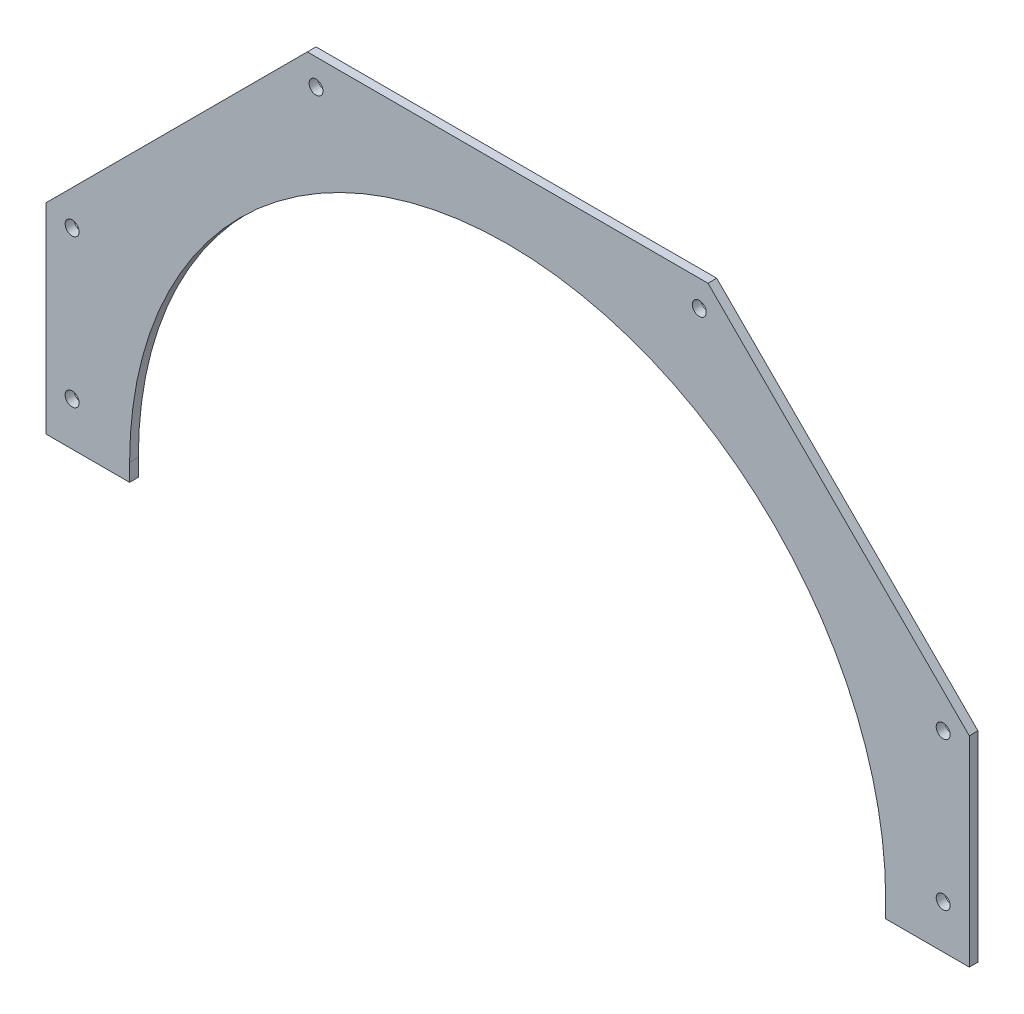
SolidWorks part; units mm, degrees
material "Q235"
ref_plane "前视基准面" through (0, 0, 0) normal (0, 0, 1) x (1, 0, 0)
ref_plane "上视基准面" through (0, 0, 0) normal (0, 1, 0) x (1, 0, 0)
ref_plane "右视基准面" through (0, 0, 0) normal (1, 0, 0) x (0, 0, -1)
sketch "草图1" plane through (0, 0, 0) normal (0, 0, 1) x (1, 0, 0)
  line L1 (0, 0) -> (1060, 0)
  line L2 (0, 0) -> (0, 530)
  line L3 (0, 530) -> (1060, 530)
  line L4 (1060, 0) -> (1060, 530)
  dimension "D1" = 1060
  dimension "D2" = 530
extrude "凸台-拉伸1" add sketch "草图1" along normal blind 10
sketch "草图2" plane through (0, 0, 10) normal (0, 0, 1) x (1, 0, 0)
  line L0 (530, 530) -> (530, -47.7641) construction
  line L1 (1060, 530) -> (0, 530) construction
  line L2 (96, 20) -> (96, 0)
  line L4 (0, 0) -> (1060, 0) construction
  line L5 (96, 0) -> (964, 0)
  line L6 (964, 20) -> (964, 0)
  arc A0 (964, 20) -> (96, 20) centre (530, 20) ccw
  dimension "D2" = 868
  dimension "D1" = 510
extrude "切除-拉伸1" cut sketch "草图2" against normal blind 10
chamfer "倒角1" distance 300 angle 45 2 edges at (0, 530, 5) (1060, 530, 5)
hole_wizard "Ø16.0 (16) 直径孔1" positions "草图3" profile "草图4" hole size "Ø16.0" standard "GB"
sketch "草图3" plane through (0, 0, 10) normal (0, 0, 1) x (1, 0, 0)
  line L0 (530, 20) -> (530, 642.5005) construction
  line L3 (0, 0) -> (96, 0) construction
  line L4 (760, 530) -> (300, 530) construction
  point P0 (30, 220)
  point P2 (30, 50)
  point P4 (1030, 220)
  point P6 (1030, 50)
  point P8 (310, 500)
  point P10 (750, 500)
  point P31 (0, 0)
  dimension "D1" = 500
  dimension "D2" = 50
  dimension "D3" = 170
  dimension "D4" = 220
  dimension "D5" = 30
sketch "草图4" plane through (30, 220, 10) normal (1, 0, 0) x (0, -1, 0)
  line L0 (0, 0) -> (0, 46.8069)
  line L1 (0, 46.8069) -> (8, 42)
  line L2 (8, 42) -> (8, 0)
  line L5 (8, 0) -> (0, 0)
  line L10 (0, 46.8069) -> (-8, 42) construction
  line L11 (0, -6.35) -> (0, 107.95) construction
  dimension "孔直径" = 16
  dimension "孔深度" = 42
  dimension "导头角度" = 118
